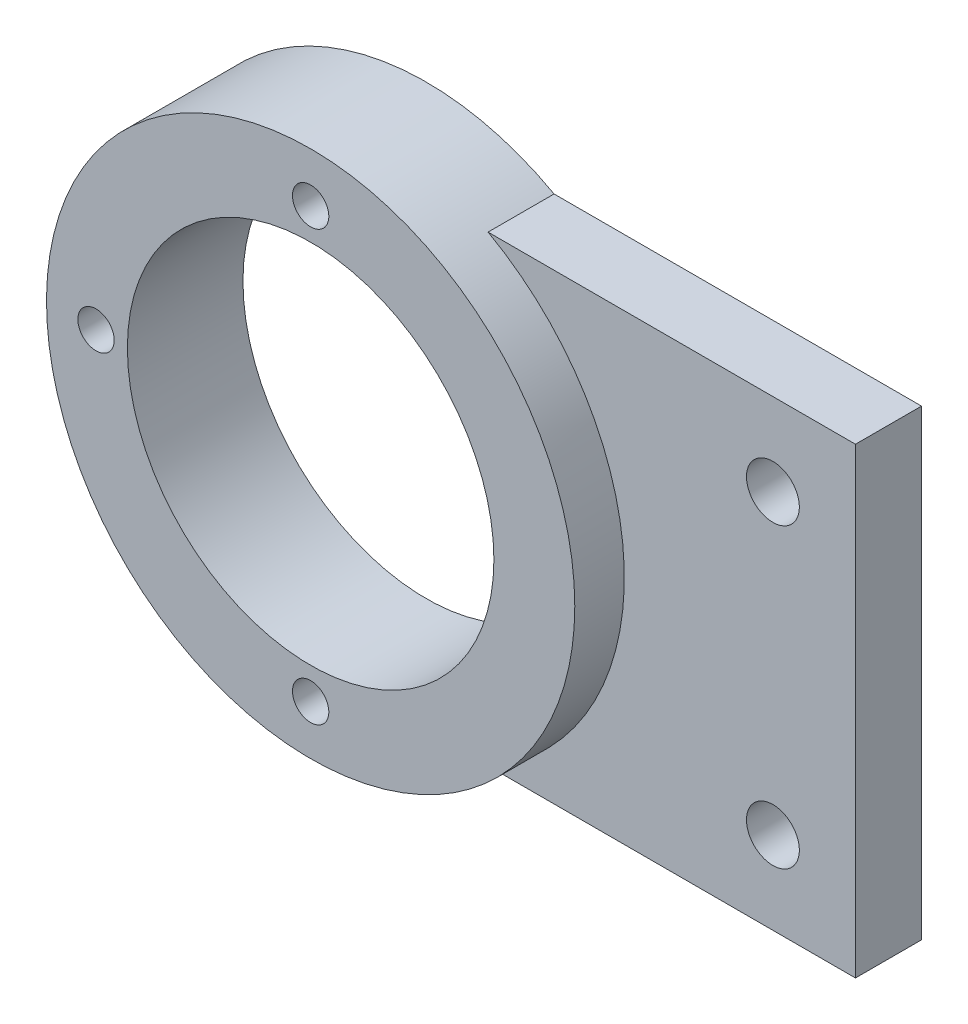
SolidWorks part; units mm, degrees
ref_plane "Front Plane" through (0, 0, 0) normal (0, 0, 1) x (1, 0, 0)
ref_plane "Top Plane" through (0, 0, 0) normal (0, 1, 0) x (1, 0, 0)
ref_plane "Right Plane" through (0, 0, 0) normal (1, 0, 0) x (0, 0, -1)
sketch "Bearing_housing_profile" plane through (0, 0, 0) normal (0, 0, 1) x (1, 0, 0)
  circle A0 centre (0, 0) radius 16
  circle A1 centre (0, 0) radius 11.1
extrude "Bearing_housing" add sketch "Bearing_housing_profile" along normal blind 7
sketch "Mounting_web_profile" plane through (0, 0, 0) normal (0, 0, 1) x (1, 0, 0)
  line L1 (0, -14) -> (30, -14)
  line L2 (0, -14) -> (0, 14)
  line L3 (0, 14) -> (30, 14)
  line L4 (30, -14) -> (30, 14)
extrude "Mounting_web" add sketch "Mounting_web_profile" along normal blind 4
sketch "Bearing_seat_profile" plane through (0, 0, 0) normal (0, 0, 1) x (1, 0, 0)
  circle A0 centre (0, 0) radius 11.1
extrude "Bearing_seat" cut sketch "Bearing_seat_profile" along normal through all from offset 50
sketch "Standoff_fasteners_profile" plane through (0, 0, 0) normal (0, 0, 1) x (1, 0, 0)
  circle A0 centre (25, -9) radius 1.6
  circle A1 centre (25, 9) radius 1.6
extrude "Standoff_fasteners" cut sketch "Standoff_fasteners_profile" along normal through all from offset 50
sketch "Bearing_keeper_fasteners_profile" plane through (0, 0, 0) normal (0, 0, 1) x (1, 0, 0)
  circle A0 centre (-13, 0) radius 1.1
  circle A1 centre (0, -13) radius 1.1
  circle A2 centre (0, 13) radius 1.1
extrude "Bearing_keeper_fasteners" cut sketch "Bearing_keeper_fasteners_profile" along normal through all from offset 50
